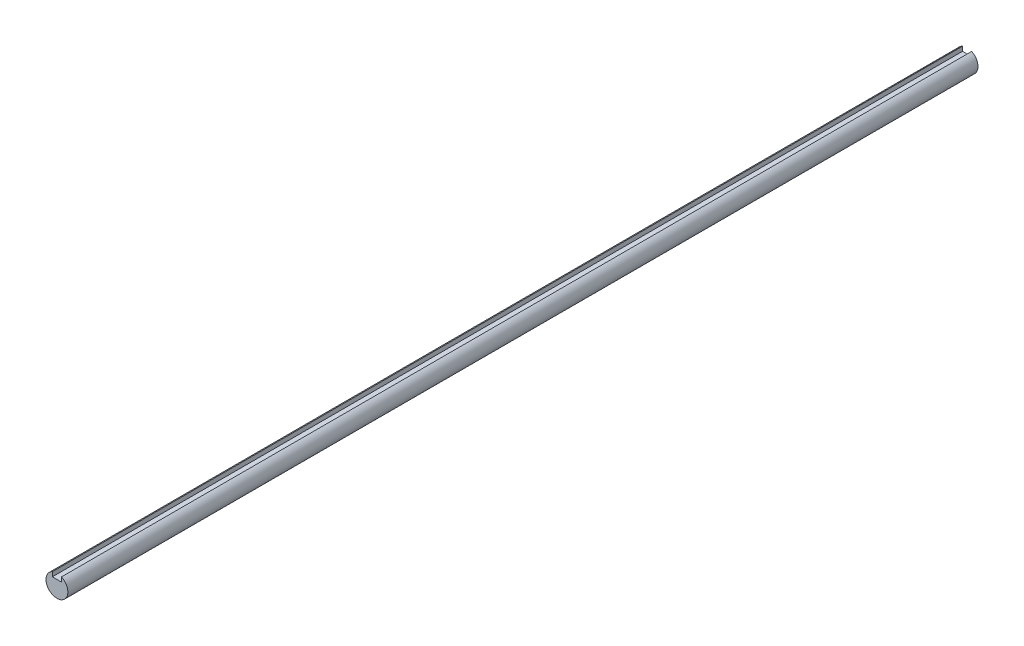
SolidWorks part; units mm, degrees
ref_plane "前视基准面" through (0, 0, 0) normal (0, 0, 1) x (1, 0, 0)
ref_plane "上视基准面" through (0, 0, 0) normal (0, 1, 0) x (1, 0, 0)
ref_plane "右视基准面" through (0, 0, 0) normal (1, 0, 0) x (0, 0, -1)
other "Configuration Table"
sketch "草图1" plane through (0, 0, 0) normal (0, 0, 1) x (1, 0, 0)
  circle A0 centre (0, 0) radius 6
  dimension "D1" = 12
extrude "凸台-拉伸1" add sketch "草图1" along normal mid plane 500
sketch "草图2" plane through (0, 0, 250) normal (0, 0, 1) x (1, 0, 0)
  line L0 (0, 0) -> (0, 9.3556) construction
  line L1 (2.5, 3) -> (-2.5, 3)
  line L2 (-2.5, 3) -> (-2.5, 5.4544)
  line L3 (2.5, 3) -> (2.5, 5.4544)
  circle A0 centre (0, 0) radius 6 construction
  arc A1 (2.5, 5.4544) -> (-2.5, 5.4544) centre (0, 0) ccw
  point P9 (0, 3)
  dimension "D1" = 5
  dimension "D2" = 3
extrude "切除-拉伸1" cut sketch "草图2" against normal through all
